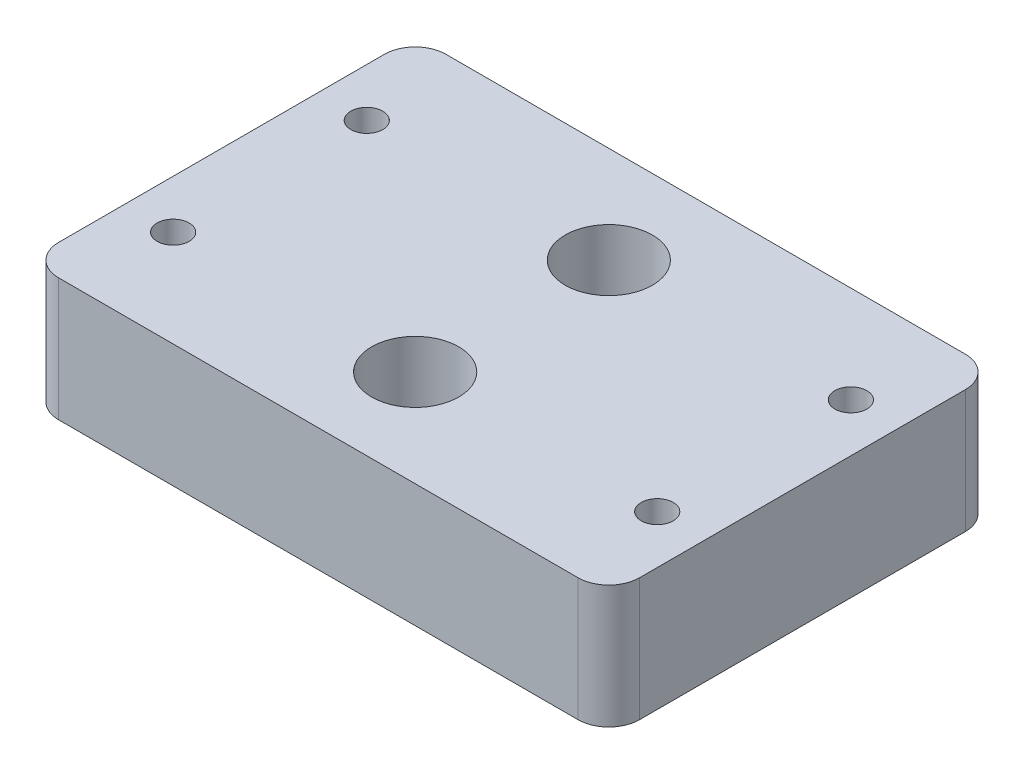
SolidWorks part; units mm, degrees
material "6061 Alloy"
ref_plane "Front Plane" through (0, 0, 0) normal (0, 0, 1) x (1, 0, 0)
ref_plane "Top Plane" through (0, 0, 0) normal (0, 1, 0) x (1, 0, 0)
ref_plane "Right Plane" through (0, 0, 0) normal (1, 0, 0) x (0, 0, -1)
sketch "Sketch1" plane through (0, 0, 0) normal (0, 1, 0) x (1, 0, 0)
  line L6 (30, -10) -> (30, -30) construction
  line L9 (5, -10) -> (55, -10) construction
  line L16 (0, 0) -> (60, 0)
  line L21 (0, 0) -> (0, -40)
  line L22 (0, -40) -> (60, -40)
  line L23 (60, 0) -> (60, -40)
  line L24 (5, -30) -> (55, -30) construction
  line L25 (15, -18) -> (45, -18) construction
  line L26 (15, -18) -> (15, -38) construction
  line L27 (15, -38) -> (45, -38) construction
  line L28 (45, -18) -> (45, -38) construction
  circle A1 centre (30, -30) radius 4.5
  circle A16 centre (30, -10) radius 4.5
  circle A20 centre (5, -10) radius 1.651
  circle A21 centre (55, -10) radius 1.651
  circle A22 centre (5, -30) radius 1.651
  circle A23 centre (55, -30) radius 1.651
  point P12 (30, 0)
  point P19 (30, -18)
  point P29 (30, -10)
  dimension "D1" = 9
  dimension "D2" = 20
  dimension "D3" = 50
  dimension "D11" = 2
  dimension "D4" = 3.302
  dimension "D8" = 60
  dimension "D6" = 8
  dimension "D7" = 40
  dimension "D9" = 30
  dimension "D10" = 20
  dimension "D12" = 12
  dimension "D5" = 10
extrude "Boss-Extrude1" add sketch "Sketch1" along normal blind 12.7
fillet "Fillet1" radius 3.175 4 edges at (0, 6.35, 40) (60, 6.35, 40) (60, 6.35, 0) (0, 6.35, 0)
